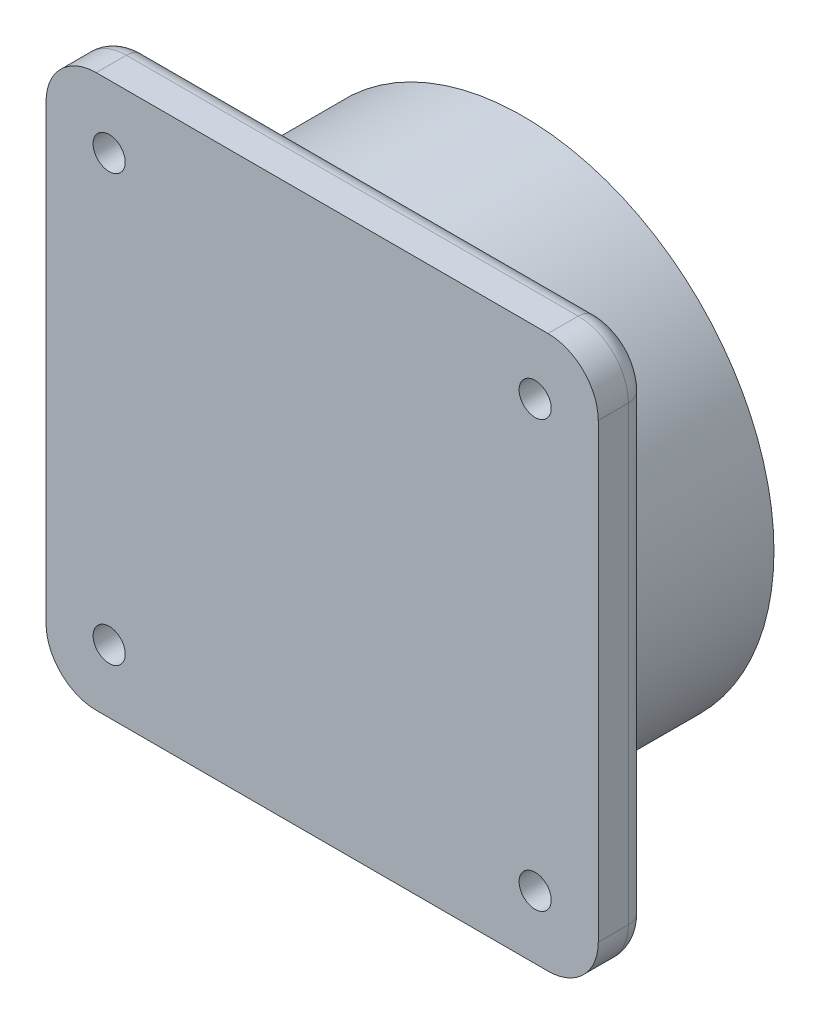
SolidWorks part; units mm, degrees
ref_plane "Płaszczyzna przednia" through (0, 0, 0) normal (0, 0, 1) x (1, 0, 0)
ref_plane "Płaszczyzna górna" through (0, 0, 0) normal (0, 1, 0) x (1, 0, 0)
ref_plane "Płaszczyzna prawa" through (0, 0, 0) normal (1, 0, 0) x (0, 0, -1)
sketch "Szkic1" plane through (0, 0, 0) normal (0, 0, 1) x (1, 0, 0)
  circle A0 centre (0, 0) radius 22.6
  circle A1 centre (0, 0) radius 25
  dimension "D1" = 45.2
  dimension "D2" = 50
extrude "Dodanie-wyciągnięcie1" add sketch "Szkic1" along normal blind 15
sketch "Szkic2" plane through (0, 0, 15) normal (0, 0, 1) x (1, 0, 0)
  line L1 (-22.5, 27.5) -> (22.5, 27.5)
  line L2 (-27.5, 22.5) -> (-27.5, -22.5)
  line L3 (-22.5, -27.5) -> (22.5, -27.5)
  line L4 (27.5, 22.5) -> (27.5, -22.5)
  line L5 (-27.5, 27.5) -> (27.5, -27.5) construction
  line L6 (-27.5, -27.5) -> (27.5, 27.5) construction
  circle A0 centre (-21.2132, 21.2132) radius 1.6
  circle A1 centre (21.2132, 21.2132) radius 1.6
  circle A2 centre (21.2132, -21.2132) radius 1.6
  circle A3 centre (-21.2132, -21.2132) radius 1.6
  arc A4 (-27.5, -22.5) -> (-22.5, -27.5) centre (-22.5, -22.5) ccw
  arc A5 (22.5, -27.5) -> (27.5, -22.5) centre (22.5, -22.5) ccw
  arc A6 (22.5, 27.5) -> (27.5, 22.5) centre (22.5, 22.5) cw
  arc A7 (-22.5, 27.5) -> (-27.5, 22.5) centre (-22.5, 22.5) ccw
  point P0 (0, 0)
  point P17 (0, 0)
  dimension "D3" = 3.2
  dimension "D5" = 4
  dimension "D6" = 5
  dimension "D1" = 55
  dimension "D2" = 55
  dimension "D4" = 30
extrude "Dodanie-wyciągnięcie2" add sketch "Szkic2" along normal blind 5
fillet "Zaokrąglenie3" radius 2 8 edges at (-26.0355, 26.0355, 15) (0, 27.5, 15) (26.0355, 26.0355, 15) (27.5, 0, 15) (26.0355, -26.0355, 15) (0, -27.5, 15) (-26.0355, -26.0355, 15) (-27.5, 0, 15)
fillet "Zaokrąglenie4" radius 1 1 edges at (25, 0, 15)
chamfer "Sfazowanie1" distance 2 angle 30 1 edges at (22.6, 0, 0)
